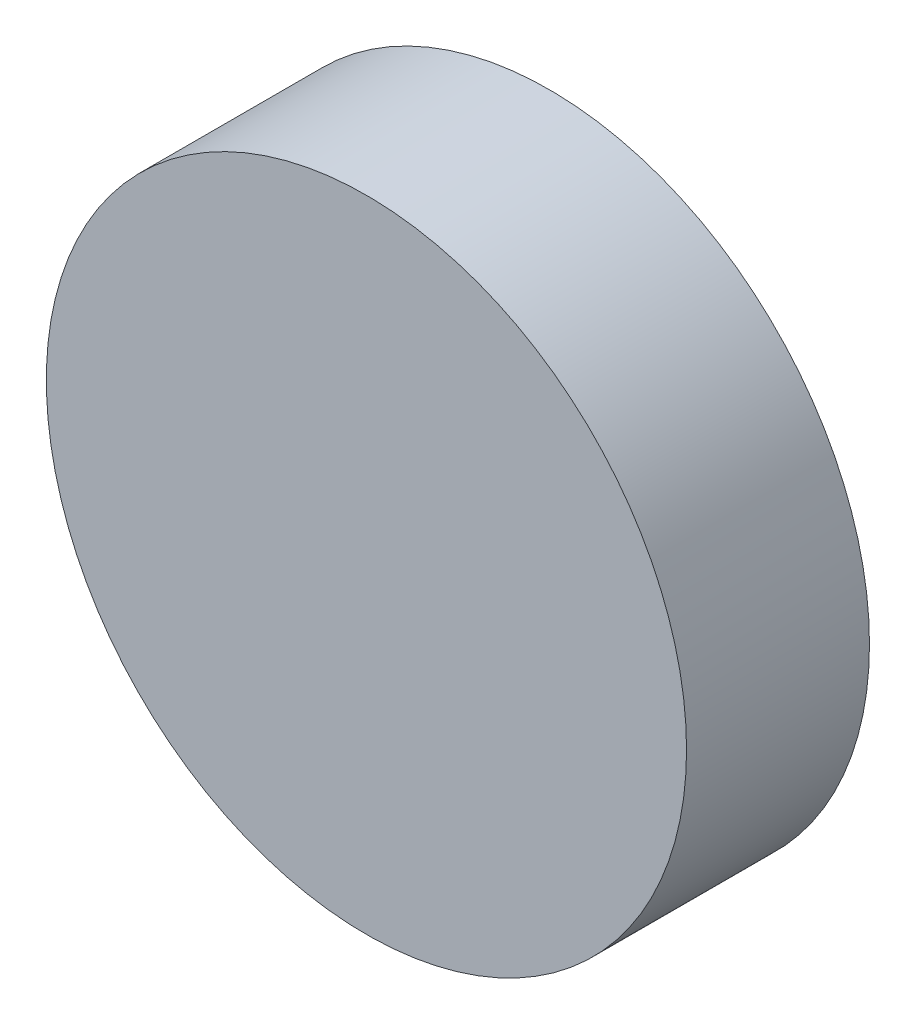
SolidWorks part; units mm, degrees
ref_plane "Front" through (0, 0, 0) normal (0, 0, 1) x (1, 0, 0)
ref_plane "Top" through (0, 0, 0) normal (0, 1, 0) x (1, 0, 0)
ref_plane "Right" through (0, 0, 0) normal (1, 0, 0) x (0, 0, -1)
sketch "Sketch1" plane through (0, 0, 0) normal (0, 0, 1) x (1, 0, 0)
  circle A0 centre (0, 0) radius 17.5
  dimension "D1" = 35
extrude "Boss-Extrude1" add sketch "Sketch1" along normal blind 10
